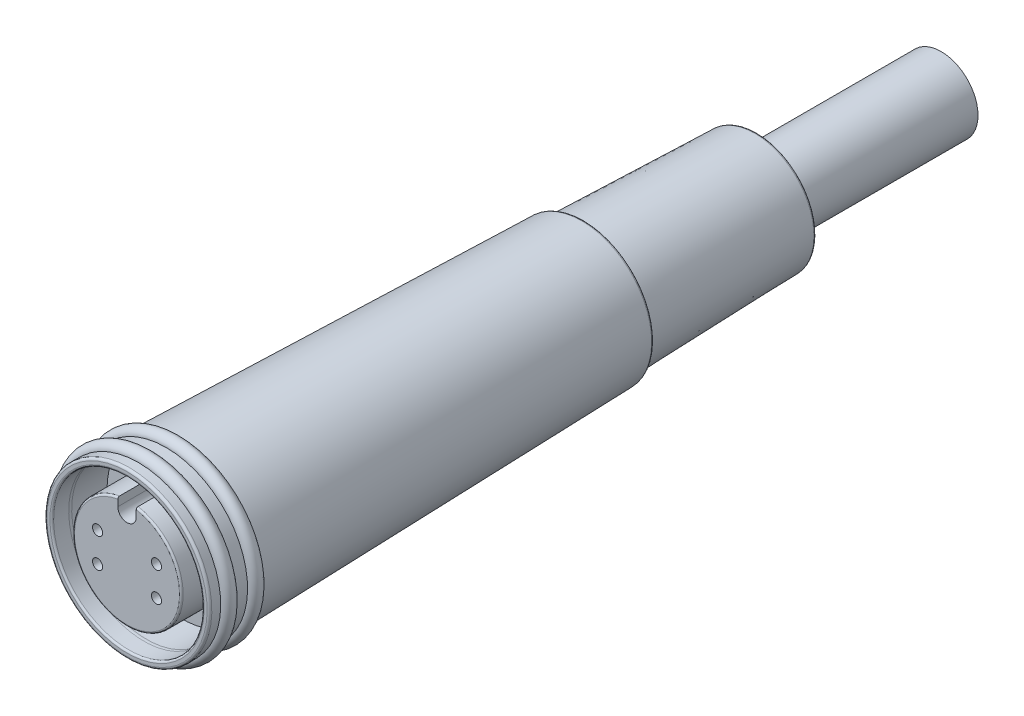
SolidWorks part; units mm, degrees
ref_plane "Front Plane" through (0, 0, 0) normal (0, 0, 1) x (1, 0, 0)
ref_plane "Top Plane" through (0, 0, 0) normal (0, 1, 0) x (1, 0, 0)
ref_plane "Right Plane" through (0, 0, 0) normal (1, 0, 0) x (0, 0, -1)
sketch "Sketch1" plane through (0, 0, 0) normal (1, 0, 0) x (0, 0, -1)
  line L1 (0.1305, 4.475) -> (24.6765, 3.8034)
  line L2 (24.8, 3.6764) -> (24.8, 3.6232)
  line L3 (24.9231, 3.4962) -> (34.0769, 3.2169)
  line L4 (34.2, 3.0899) -> (34.2, 0)
  line L5 (34.2, 0) -> (0, 0)
  line L6 (0, 4.348) -> (0, 4.185)
  line L7 (0.1, 4.085) -> (3, 4.085)
  line L8 (3, 4.085) -> (3, 2.95)
  line L9 (0, 2.85) -> (0, 0)
  line L11 (34.2, 2) -> (59.2, 2)
  line L12 (59.2, 2) -> (59.2, 0)
  line L13 (59.2, 0) -> (34.2, 0)
  line L14 (0.1, 2.95) -> (3, 2.95)
  arc A0 (34.0769, 3.2169) -> (34.2, 3.0899) centre (34.073, 3.0899) cw
  arc A1 (24.8, 3.6232) -> (24.9231, 3.4962) centre (24.927, 3.6232) ccw
  arc A2 (24.6765, 3.8034) -> (24.8, 3.6764) centre (24.673, 3.6764) cw
  arc A3 (0, 4.348) -> (0.1305, 4.475) centre (0.127, 4.348) cw
  circle A4 centre (1, 4.4512) radius 0.375
  circle A5 centre (2.5, 4.4102) radius 0.375
  arc A13 (0, 4.185) -> (0.1, 4.085) centre (0.1, 4.185) ccw
  arc A15 (0, 2.85) -> (0.1, 2.95) centre (0.1, 2.85) cw
  point P9 (34.2, 3.2131)
  point P12 (24.8, 3.5)
  point P15 (24.8, 3.8)
  point P18 (0, 4.5)
  dimension "D7" = 0.127
  dimension "D12" = 0.75
  dimension "D8" = 1
  dimension "D3" = 0.1
  dimension "D1" = 3.8
  dimension "D2" = 4.5
  dimension "D4" = 3.5
  dimension "D5" = 3.2131
  dimension "D6" = 4.085
  dimension "D9" = 2.5
  dimension "D10" = 4.475
  dimension "D11" = 2.95
  dimension "D13" = 24.8
  dimension "D14" = 3
  dimension "D15" = 34.2
  dimension "D19" = 2
  dimension "D20" = 25
revolve "Revolve1" add sketch "Sketch1" angle 360 about L5
sketch "Sketch2" plane through (0, 0, 0) normal (0, 0, 1) x (1, 0, 0)
  line L0 (0, 2.95) -> (0, 2.45) construction
  line L1 (0.5, 2.95) -> (0.5, 2.45)
  line L2 (-0.5, 2.95) -> (-0.5, 2.45)
  line L3 (-1.6, 0.8) -> (-1.6, -0.8) construction
  line L4 (0, -5.3088) -> (0, 5.3088) construction
  circle A0 centre (0, 0) radius 2.95 construction
  arc A2 (0.5, 2.95) -> (-0.5, 2.95) centre (0, 2.95) ccw
  arc A3 (-0.5, 2.45) -> (0.5, 2.45) centre (0, 2.45) ccw
  circle A4 centre (-1.6, 0.8) radius 0.275
  circle A5 centre (-1.6, -0.8) radius 0.275
  circle A6 centre (1.6, -0.8) radius 0.275
  circle A7 centre (1.6, 0.8) radius 0.275
  point P7 (0, 2.7)
  point P14 (-1.6, 0)
  dimension "D2" = 0.55
  dimension "D4" = 0.5
  dimension "D1" = 1.6
  dimension "D3" = 1.6
  dimension "D5" = 0.5
sketch "Sketch3" plane through (0, 0, 0) normal (1, 0, 0) x (0, 0, -1)
  line L3 (19.1545, 22.7383) -> (20.1817, 18.9047) construction
  line L8 (44.2, 0) -> (34.2, 0)
  line L9 (34.2, -3.0899) -> (34.2, 3.0899) construction
  point P7 (19.6681, 20.8215)
  dimension "D4" = 10
sweep "Sweep4" add path "Sketch3" circular profile diameter 4 parameters "D3"=4
extrude "Cut-Extrude1" cut sketch "Sketch2" against normal up to surface (3 mm away) up to face at (0, 2.95, -3)
